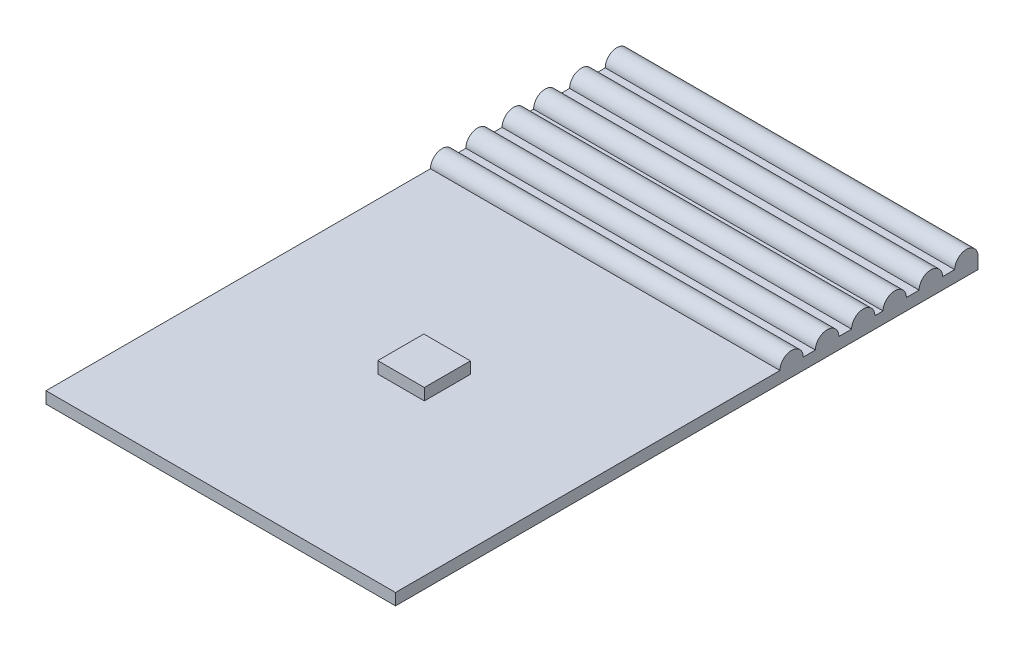
SolidWorks part; units mm, degrees
ref_plane "Front Plane" through (0, 0, 0) normal (0, 0, 1) x (1, 0, 0)
ref_plane "Top Plane" through (0, 0, 0) normal (0, 1, 0) x (1, 0, 0)
ref_plane "Right Plane" through (0, 0, 0) normal (1, 0, 0) x (0, 0, -1)
sketch "Sketch1" plane through (0, 0, 0) normal (0, 1, 0) x (1, 0, 0)
  line L1 (0, 0) -> (30, 0)
  line L2 (0, 0) -> (0, 50)
  line L3 (0, 50) -> (30, 50)
  line L4 (30, 0) -> (30, 50)
extrude "Boss-Extrude1" add sketch "Sketch1" along normal blind 1
sketch "Sketch2" plane through (0, 1, 0) normal (0, 1, 0) x (1, 0, 0)
  line L0 (30, 0) -> (30, 50) construction
  line L1 (0, 50) -> (30, 50)
  line L2 (0, 50) -> (0, 25)
  line L3 (0, 25) -> (30, 25)
  line L4 (30, 50) -> (30, 25)
  line L5 (0, 50) -> (0, 49.039)
sketch "Sketch3" plane through (0, 0, 0) normal (-1, 0, 0) x (0, 0, 1)
  line L0 (-50, 1) -> (-49.039, 1) construction
  line L1 (-50, 1) -> (-48, 1)
  arc A0 (-48, 1) -> (-50, 1) centre (-49, 1) ccw
extrude "Boss-Extrude2" add sketch "Sketch3" against normal blind 30
sketch "Sketch4" plane through (0, 1, 0) normal (0, 1, 0) x (1, 0, 0)
  line L0 (0, 48) -> (0, 46.0063)
  line L1 (0, 50) -> (0, 25) construction
sketch "Sketch5" plane through (0, 0, 0) normal (-1, 0, 0) x (0, 0, 1)
  line L0 (-50, 1) -> (-25, 1) construction
  line L1 (-46.9606, 1) -> (-44.9462, 1)
  arc A0 (-44.9462, 1) -> (-46.9606, 1) centre (-45.9534, 1) ccw
extrude "Boss-Extrude3" add sketch "Sketch5" against normal blind 30
sketch "Sketch6" plane through (0, 1, 0) normal (0, 1, 0) x (1, 0, 0)
  line L0 (0, 44.9462) -> (0, 42.9462)
  line L1 (0, 50) -> (0, 25) construction
sketch "Sketch7" plane through (0, 0, 0) normal (-1, 0, 0) x (0, 0, 1)
  line L0 (-50, 1) -> (-25, 1) construction
  line L1 (-43.8511, 1) -> (-41.8511, 1)
  arc A0 (-41.8511, 1) -> (-43.8511, 1) centre (-42.8511, 1) ccw
extrude "Boss-Extrude5" add sketch "Sketch7" against normal blind 30
ref_plane "Plane1" through (0, 0, -41.5) normal (0, 0, -1) x (-1, 0, 0)
mirror "Mirror1" about plane through (0, 0, -41.5) normal (0, 0, -1) of "Boss-Extrude5", "Boss-Extrude3", "Boss-Extrude2"
sketch "Sketch8" plane through (0, 1, 0) normal (0, 1, 0) x (1, 0, 0)
  line L6 (13, 15.4765) -> (17, 15.4765)
  line L7 (13, 15.4765) -> (13, 19.4312)
  line L8 (13, 19.4312) -> (17, 19.4312)
  line L9 (17, 15.4765) -> (17, 19.4312)
extrude "Boss-Extrude6" add sketch "Sketch8" along normal blind 1
